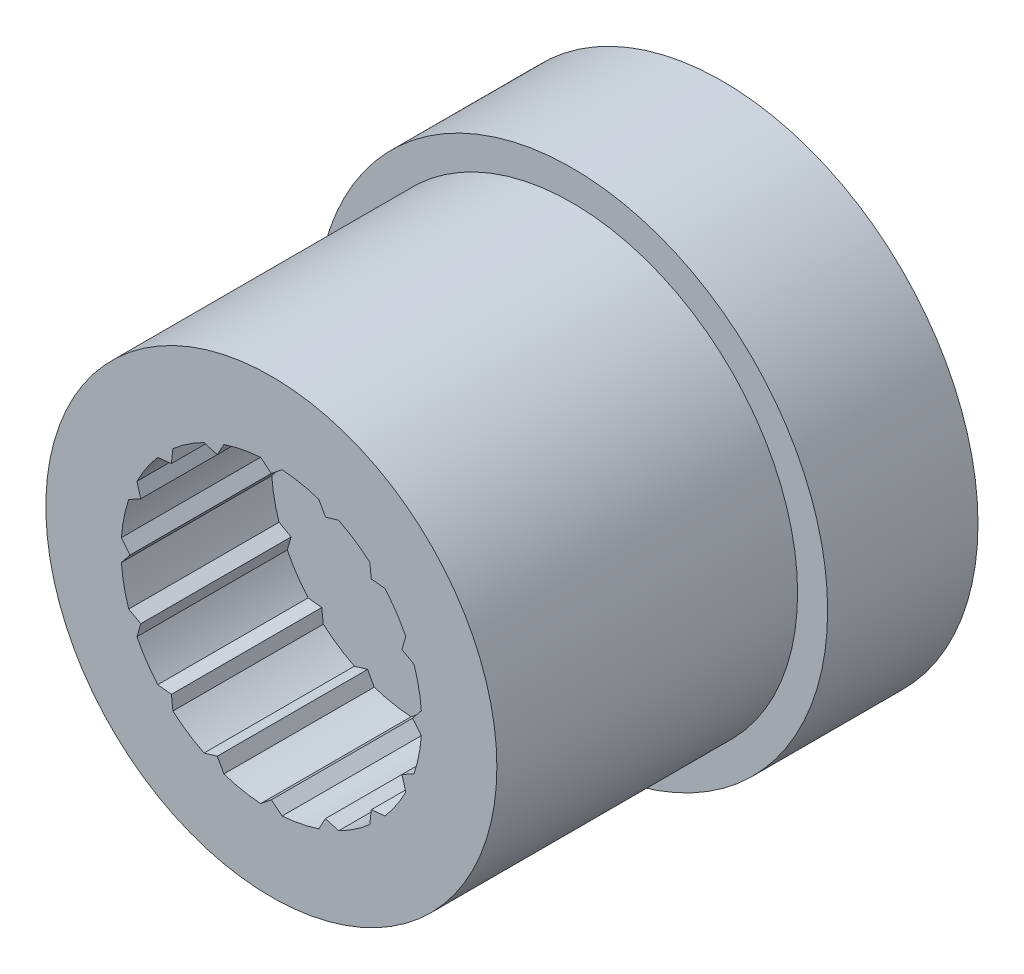
SolidWorks part; units mm, degrees
ref_plane "Front Plane" through (0, 0, 0) normal (0, 0, 1) x (1, 0, 0)
ref_plane "Top Plane" through (0, 0, 0) normal (0, 1, 0) x (1, 0, 0)
ref_plane "Right Plane" through (0, 0, 0) normal (1, 0, 0) x (0, 0, -1)
sketch "Sketch1" plane through (0, 0, 0) normal (0, 0, 1) x (1, 0, 0)
  circle A0 centre (0, 0) radius 8.5
  dimension "D1" = 17
extrude "Boss-Extrude1" add sketch "Sketch1" along normal blind 5
sketch "Sketch2" plane through (0, 0, 5) normal (0, 0, 1) x (1, 0, 0)
  circle A0 centre (0, 0) radius 7.5
  dimension "D1" = 15
extrude "Boss-Extrude2" add sketch "Sketch2" along normal blind 10
sketch "Sketch3" plane through (0, 0, 15) normal (0, 0, 1) x (1, 0, 0)
  circle A0 centre (0, 0) radius 5
  dimension "D1" = 10
extrude "Cut-Extrude1" cut sketch "Sketch3" against normal blind 5
sketch "Sketch4" plane through (0, 0, 15) normal (0, 0, 1) x (1, 0, 0)
  line L0 (-4.7, 0) -> (-5.3027, 0.75)
  line L5 (-5.3027, 0) -> (-4.7, 0) construction
  line L6 (0, 0) -> (-5, 0) construction
  line L7 (-5.3027, 0.75) -> (-5.3027, -0.75)
  line L8 (-5.3027, -0.75) -> (-4.7, 0)
  line L9 (-4.6121, 2.7222) -> (-5.1861, 1.3364)
  line L10 (-4.3422, 1.7986) -> (-4.6121, 2.7222)
  line L11 (-5.1861, 1.3364) -> (-4.3422, 1.7986)
  line L12 (-3.2193, 4.2799) -> (-4.2799, 3.2193)
  line L13 (-3.3234, 3.3234) -> (-3.2193, 4.2799)
  line L14 (-4.2799, 3.2193) -> (-3.3234, 3.3234)
  line L15 (-1.3364, 5.1861) -> (-2.7222, 4.6121)
  line L16 (-1.7986, 4.3422) -> (-1.3364, 5.1861)
  line L17 (-2.7222, 4.6121) -> (-1.7986, 4.3422)
  line L18 (0.75, 5.3027) -> (-0.75, 5.3027)
  line L19 (0, 4.7) -> (0.75, 5.3027)
  line L20 (-0.75, 5.3027) -> (0, 4.7)
  line L21 (2.7222, 4.6121) -> (1.3364, 5.1861)
  line L22 (1.7986, 4.3422) -> (2.7222, 4.6121)
  line L23 (1.3364, 5.1861) -> (1.7986, 4.3422)
  line L24 (4.2799, 3.2193) -> (3.2193, 4.2799)
  line L25 (3.3234, 3.3234) -> (4.2799, 3.2193)
  line L26 (3.2193, 4.2799) -> (3.3234, 3.3234)
  line L27 (5.1861, 1.3364) -> (4.6121, 2.7222)
  line L28 (4.3422, 1.7986) -> (5.1861, 1.3364)
  line L29 (4.6121, 2.7222) -> (4.3422, 1.7986)
  line L30 (5.3027, -0.75) -> (5.3027, 0.75)
  line L31 (4.7, 0) -> (5.3027, -0.75)
  line L32 (5.3027, 0.75) -> (4.7, 0)
  line L33 (4.6121, -2.7222) -> (5.1861, -1.3364)
  line L34 (4.3422, -1.7986) -> (4.6121, -2.7222)
  line L35 (5.1861, -1.3364) -> (4.3422, -1.7986)
  line L36 (3.2193, -4.2799) -> (4.2799, -3.2193)
  line L37 (3.3234, -3.3234) -> (3.2193, -4.2799)
  line L38 (4.2799, -3.2193) -> (3.3234, -3.3234)
  line L39 (1.3364, -5.1861) -> (2.7222, -4.6121)
  line L40 (1.7986, -4.3422) -> (1.3364, -5.1861)
  line L41 (2.7222, -4.6121) -> (1.7986, -4.3422)
  line L42 (-0.75, -5.3027) -> (0.75, -5.3027)
  line L43 (0, -4.7) -> (-0.75, -5.3027)
  line L44 (0.75, -5.3027) -> (0, -4.7)
  line L45 (-2.7222, -4.6121) -> (-1.3364, -5.1861)
  line L46 (-1.7986, -4.3422) -> (-2.7222, -4.6121)
  line L47 (-1.3364, -5.1861) -> (-1.7986, -4.3422)
  line L48 (-4.2799, -3.2193) -> (-3.2193, -4.2799)
  line L49 (-3.3234, -3.3234) -> (-4.2799, -3.2193)
  line L50 (-3.2193, -4.2799) -> (-3.3234, -3.3234)
  line L51 (-5.1861, -1.3364) -> (-4.6121, -2.7222)
  line L52 (-4.3422, -1.7986) -> (-5.1861, -1.3364)
  line L53 (-4.6121, -2.7222) -> (-4.3422, -1.7986)
  circle A2 centre (0, 0) radius 5 construction
  dimension "D1" = 1.5
  dimension "D2" = 0.3
  dimension "D3" = 16
extrude "Boss-Extrude5" add sketch "Sketch4" against normal blind 5
sketch "Sketch5" plane through (0, 0, 0) normal (0, 0, -1) x (-1, 0, 0)
  circle A0 centre (0, 0) radius 6.2708
  circle A1 centre (0, 0) radius 2.9595
extrude "Cut-Extrude2" cut sketch "Sketch5" against normal blind 1
